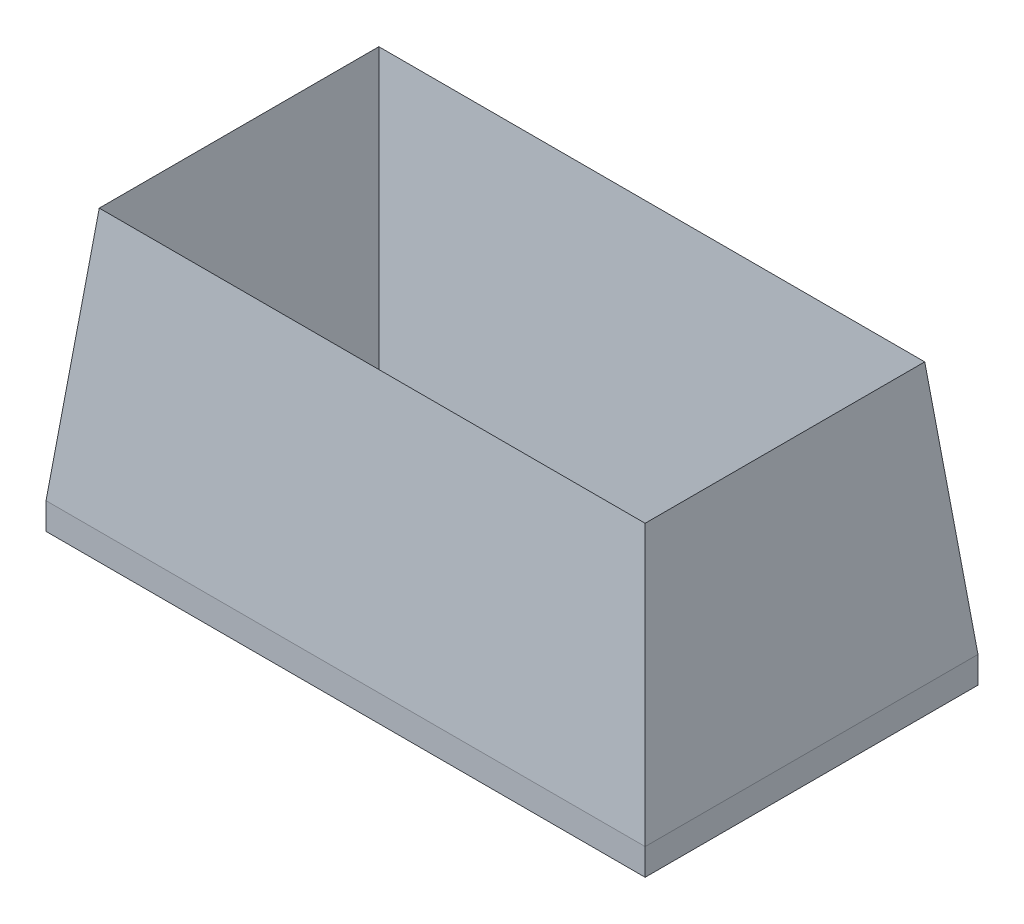
SolidWorks part; units mm, degrees
ref_plane "Front Plane" through (0, 0, 0) normal (0, 0, 1) x (1, 0, 0)
ref_plane "Top Plane" through (0, 0, 0) normal (0, 1, 0) x (1, 0, 0)
ref_plane "Right Plane" through (0, 0, 0) normal (1, 0, 0) x (0, 0, -1)
sketch "Sketch2" plane through (0, 0, 0) normal (0, 1, 0) x (1, 0, 0)
  line L1 (-22.5, 12.5) -> (22.5, 12.5)
  line L2 (-22.5, 12.5) -> (-22.5, -12.5)
  line L3 (-22.5, -12.5) -> (22.5, -12.5)
  line L4 (22.5, 12.5) -> (22.5, -12.5)
  line L5 (-22.5, 12.5) -> (22.5, -12.5) construction
  line L6 (-22.5, -12.5) -> (22.5, 12.5) construction
  point P0 (0, 0)
  dimension "D1" = 45
  dimension "D2" = 25
extrude "Boss-Extrude1" add sketch "Sketch2" along normal blind 2
sketch "Sketch3" plane through (0, 2, 0) normal (0, 1, 0) x (1, 0, 0)
  line L1 (-18.5, 8.5) -> (18.5, 8.5)
  line L2 (-18.5, 8.5) -> (-18.5, -8.5)
  line L3 (-18.5, -8.5) -> (18.5, -8.5)
  line L4 (18.5, 8.5) -> (18.5, -8.5)
  line L5 (-18.5, 8.5) -> (18.5, -8.5) construction
  line L6 (-18.5, -8.5) -> (18.5, 8.5) construction
  line L10 (22.5, -12.5) -> (22.5, 12.5)
  line L11 (22.5, 12.5) -> (-22.5, 12.5)
  line L12 (-22.5, 12.5) -> (-22.5, -12.5)
  line L13 (-22.5, -12.5) -> (22.5, -12.5)
  line L14 (22.5, -12.5) -> (22.5, 12.5)
  line L15 (22.5, 12.5) -> (-22.5, 12.5)
  line L16 (-22.5, 12.5) -> (-22.5, -12.5)
  line L17 (-22.5, -12.5) -> (22.5, -12.5)
  point P0 (0, 0)
  dimension "D1" = 37
  dimension "D2" = 17
  dimension "D3" = 0
extrude "Boss-Extrude2" add sketch "Sketch3" along normal blind 35 draft 6
